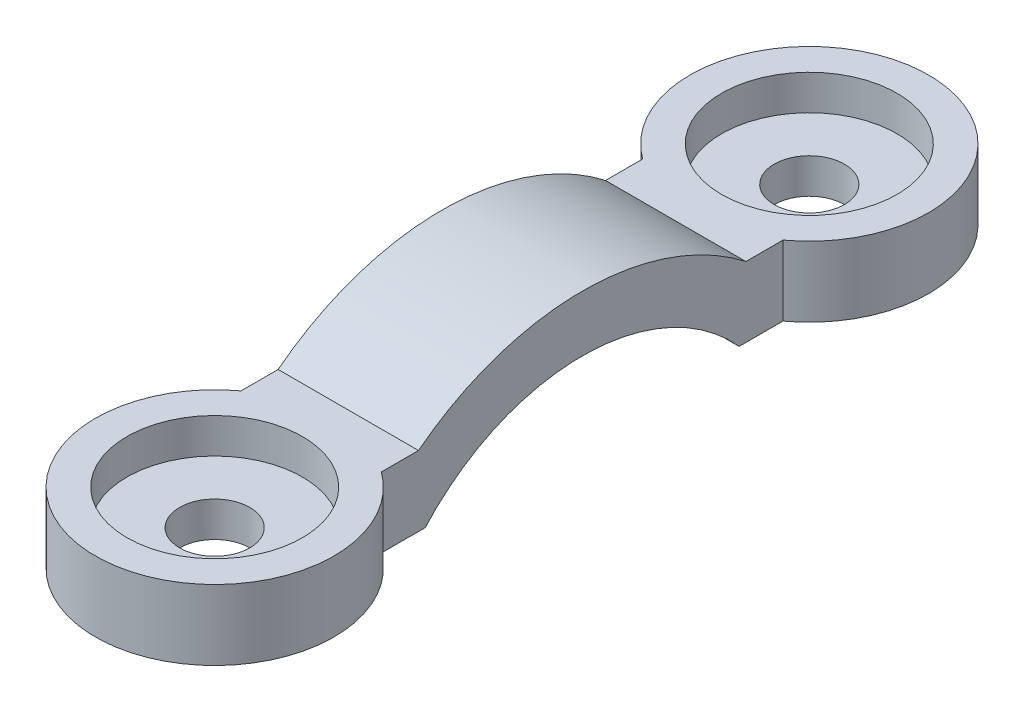
SolidWorks part; units mm, degrees
ref_plane "Plan de face" through (0, 0, 0) normal (0, 0, 1) x (1, 0, 0)
ref_plane "Plan de dessus" through (0, 0, 0) normal (0, 1, 0) x (1, 0, 0)
ref_plane "Plan de droite" through (0, 0, 0) normal (1, 0, 0) x (0, 0, -1)
sketch "Esquisse2" plane through (0, 0, 0) normal (1, 0, 0) x (0, 0, -1)
  line L0 (-16.7178, 10) -> (20.1552, 10) construction
  line L1 (-14.3614, 10) -> (-26.1803, 10)
  line L2 (-26.1803, 10) -> (-26.1803, 15)
  line L3 (-26.1803, 15) -> (-11.6619, 15)
  line L4 (14.3614, 10) -> (21.1803, 10)
  line L5 (26.1803, 15) -> (26.1803, 10)
  line L6 (26.1803, 15) -> (11.6619, 15)
  line L7 (26.1803, 10) -> (21.1803, 10)
  line L8 (-14.3614, 10) -> (-11.1803, 10)
  line L9 (11.1803, 10) -> (21.1803, 10)
  arc A0 (11.1803, 10) -> (-11.1803, 10) centre (0, 0) ccw
  arc A2 (11.6619, 15) -> (-11.6619, 15) centre (0, 0) ccw
  point P5 (-21.1803, 10)
  point P6 (21.1803, 10)
  point P7 (-11.1803, 10)
  point P8 (11.1803, 10)
  dimension "D1" = 30
  dimension "D3" = 10
  dimension "D5" = 5
  dimension "D7" = 4
  dimension "D2" = 10
  dimension "D4" = 10
  dimension "D6" = 5
  dimension "D8" = 5
  dimension "D9" = 5
extrude "BASE" add sketch "Esquisse2" along normal blind 10 contours L6 A2 L3 L2 L1 L8 A0 L9 L4 L7 L5
sketch "Esquisse5" plane through (0, 10, 0) normal (0, -1, 0) x (1, 0, 0)
  line L0 (5, 26.1803) -> (5, 11.1803) construction
  line L1 (10, 26.1803) -> (0, 26.1803) construction
  line L2 (10, 11.1803) -> (0, 11.1803) construction
  line L3 (-3.4429, 0) -> (13.3559, 0) construction
  circle A0 centre (5, 21.1803) radius 2.5
  circle A1 centre (5, -21.1803) radius 2.5
  dimension "D2" = 5
  dimension "D1" = 5
extrude "VIDE ACCES VIS" cut sketch "Esquisse5" against normal through all
sketch "Esquisse6" plane through (0, 15, 0) normal (0, 1, 0) x (1, 0, 0)
  circle A0 centre (5, 21.1803) radius 2.5
  circle A1 centre (5, -21.1803) radius 2.5
  circle A2 centre (5, -21.1803) radius 8.5
  circle A3 centre (5, 21.1803) radius 8.5
  dimension "D1" = 17
  dimension "D2" = 17
extrude "BOSS VIS" add sketch "Esquisse6" against normal up to surface (5 mm away) up to face at (5, 10, -18.6803)
sketch "Esquisse7" plane through (0, 15, 0) normal (0, 1, 0) x (1, 0, 0)
  circle A0 centre (5, 21.1803) radius 6.25
  circle A1 centre (5, -21.1803) radius 6.25
  dimension "D1" = 12.5
  dimension "D2" = 12.5
extrude "VIDE ECROU" cut sketch "Esquisse7" against normal blind 2.5
